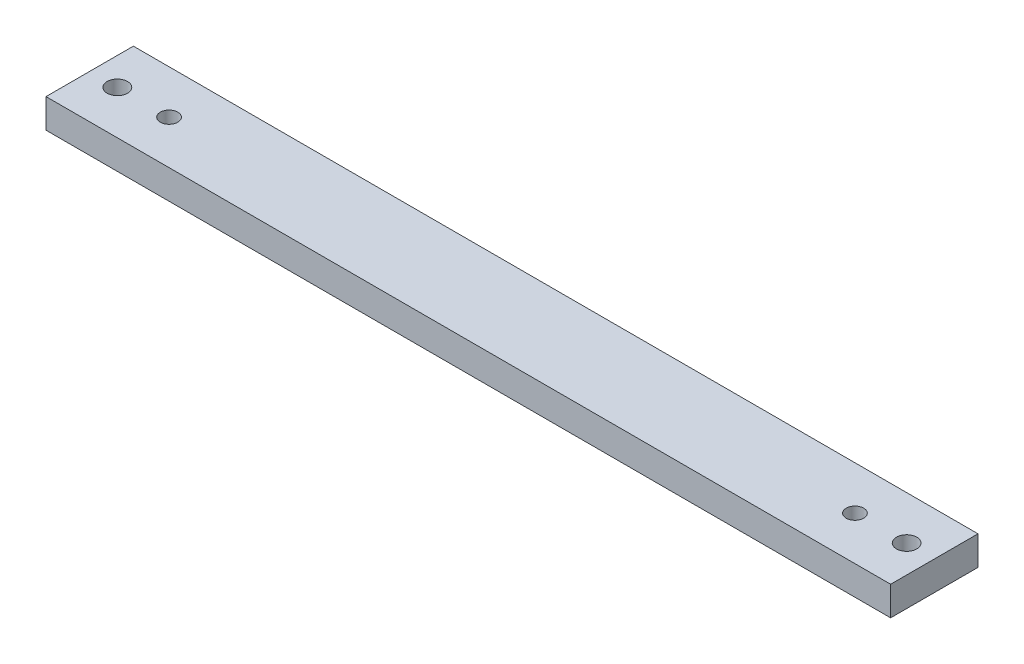
SolidWorks part; units mm, degrees
ref_plane "Front Plane" through (0, 0, 0) normal (0, 0, 1) x (1, 0, 0)
ref_plane "Top Plane" through (0, 0, 0) normal (0, 1, 0) x (1, 0, 0)
ref_plane "Right Plane" through (0, 0, 0) normal (1, 0, 0) x (0, 0, -1)
sketch "Sketch3" plane through (0, 0, 0) normal (0, 1, 0) x (1, 0, 0)
  line L1 (0, 80) -> (580, 80)
  line L2 (0, 80) -> (0, 20)
  line L3 (0, 20) -> (580, 20)
  line L4 (580, 80) -> (580, 20)
  dimension "D1" = 580
  dimension "D2" = 60
extrude "Boss-Extrude1" add sketch "Sketch3" along normal blind 20
sketch "Sketch4" plane through (0, 20, 0) normal (0, 1, 0) x (1, 0, 0)
  line L0 (580, 80) -> (0, 80) construction
  circle A0 centre (19, 50) radius 7
  circle A1 centre (54.5, 50) radius 6
  circle A2 centre (525.5, 50) radius 6
  circle A3 centre (561, 50) radius 7
  dimension "D1" = 12
  dimension "D3" = 14
  dimension "D4" = 12
  dimension "D5" = 14
  dimension "D2" = 35.5
  dimension "D6" = 35.5
  dimension "D7" = 471
  dimension "D8" = 30
  dimension "D9" = 30
extrude "Cut-Extrude1" cut sketch "Sketch4" against normal through all
